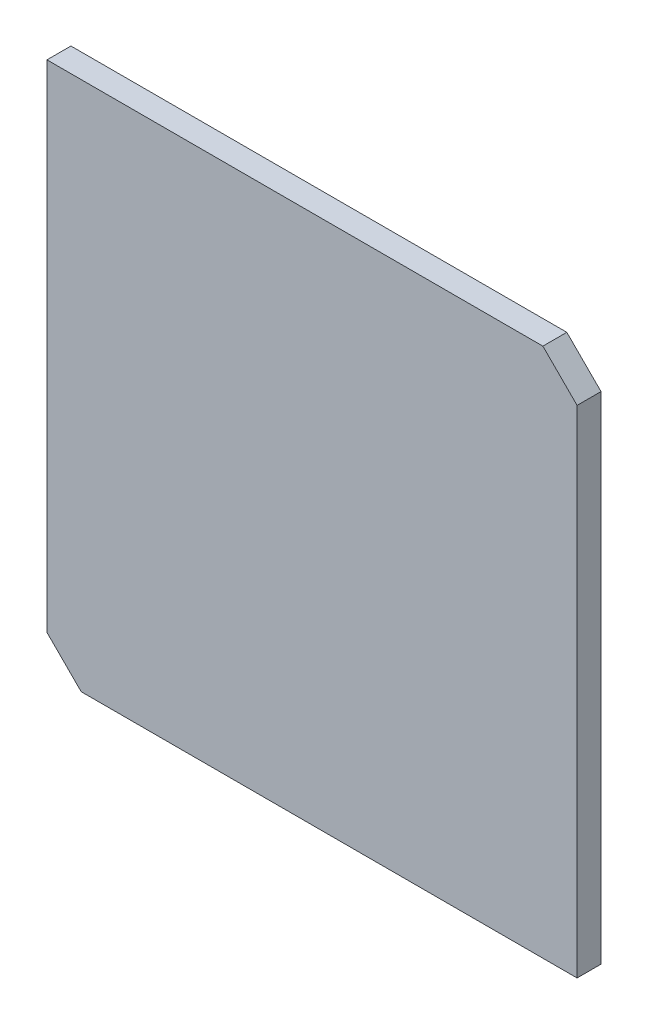
SolidWorks part; units mm, degrees
ref_plane "前视" through (0, 0, 0) normal (0, 0, 1) x (1, 0, 0)
ref_plane "上视" through (0, 0, 0) normal (0, 1, 0) x (1, 0, 0)
ref_plane "右视" through (0, 0, 0) normal (1, 0, 0) x (0, 0, -1)
sketch "草图1" plane through (0, 0, 0) normal (0, 0, 1) x (1, 0, 0)
  line L0 (-1611.3839, 0) -> (1936.635, 0) construction
  line L1 (135, 155) -> (155, 135)
  line L2 (0, 1418.2496) -> (0, -1054.9444) construction
  line L3 (-155, 155) -> (135, 155)
  line L4 (-155, 155) -> (-155, -135)
  line L5 (-135, -155) -> (155, -155)
  line L6 (155, 135) -> (155, -155)
  line L7 (-155, -135) -> (-135, -155)
  line L8 (-241.7498, -241.7498) -> (0, 0) construction
  line L9 (0, 0) -> (269.6196, 269.6196) construction
  line L10 (262.9093, -262.9093) -> (0, 0) construction
  line L11 (0, 0) -> (-278.609, 278.609) construction
  line L12 (0, 0) -> (-785, -619) construction
  line L14 (0, 0) -> (171.8618, 135.5191) construction
  dimension "D7" = 45
  dimension "D1" = 310
  dimension "D2" = 310
  dimension "D3" = 20
  dimension "D4" = 20
  dimension "D5" = 20
  dimension "D6" = 20
  dimension "D8" = 45
  dimension "D10" = 619
  dimension "D11" = 785
extrude "基体-拉伸" add sketch "草图1" along normal blind 14
